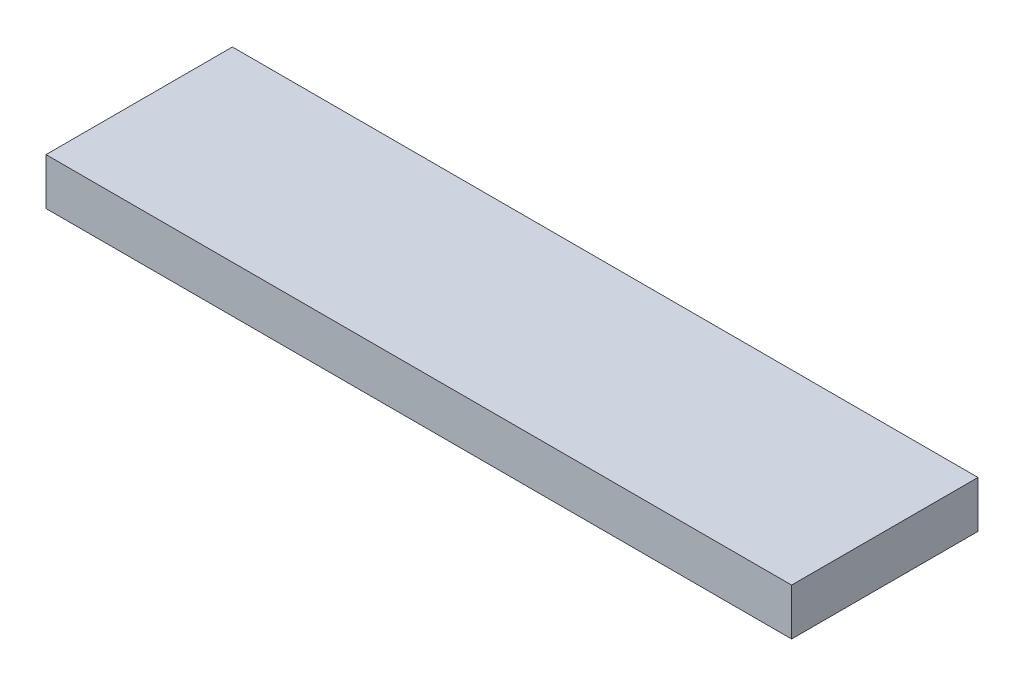
SolidWorks part; units mm, degrees
ref_plane "Front Plane" through (0, 0, 0) normal (0, 0, 1) x (1, 0, 0)
ref_plane "Top Plane" through (0, 0, 0) normal (0, 1, 0) x (1, 0, 0)
ref_plane "Right Plane" through (0, 0, 0) normal (1, 0, 0) x (0, 0, -1)
sketch "Sketch2" plane through (0, 0, 0) normal (0, 1, 0) x (1, 0, 0)
  line L1 (-38.1, -9.525) -> (38.1, -9.525)
  line L2 (-38.1, -9.525) -> (-38.1, 9.525)
  line L3 (-38.1, 9.525) -> (38.1, 9.525)
  line L4 (38.1, -9.525) -> (38.1, 9.525)
  line L5 (-38.1, -9.525) -> (38.1, 9.525) construction
  line L6 (-38.1, 9.525) -> (38.1, -9.525) construction
  point P0 (0, 0)
  dimension "D1" = 76.2
  dimension "D2" = 19.05
extrude "Boss-Extrude2" add sketch "Sketch2" along normal blind 4.7752 contours L3 L4 L1 L2
